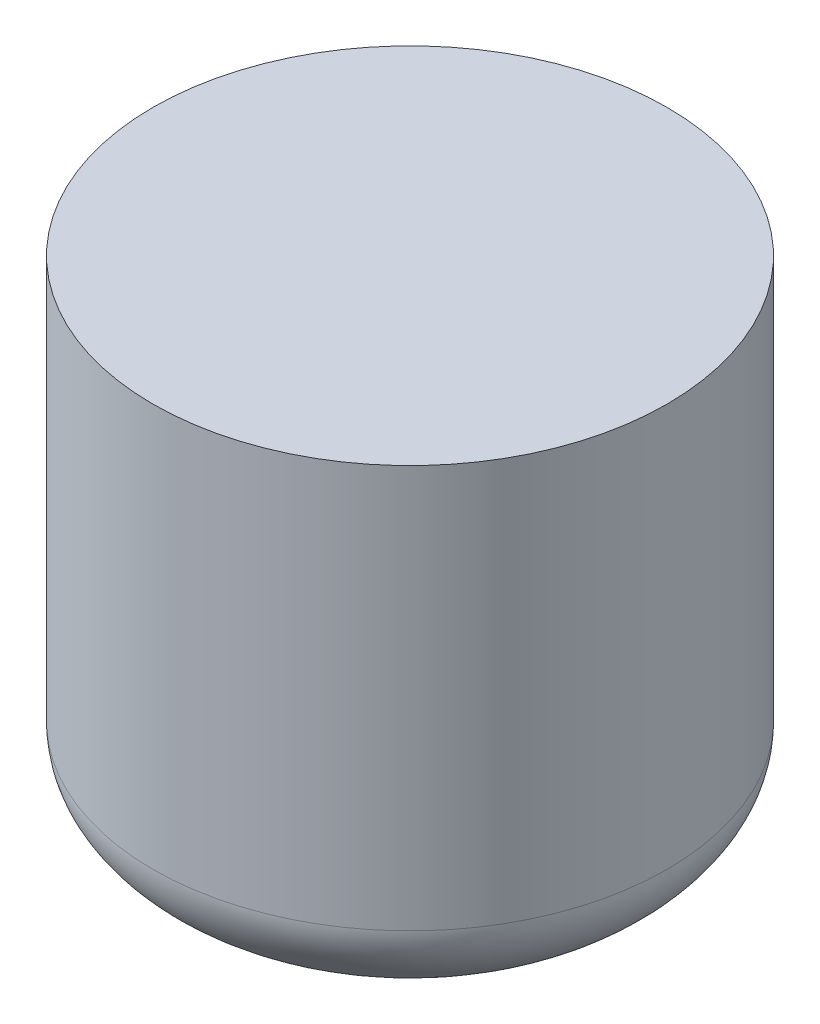
SolidWorks part; units mm, degrees
ref_plane "Front Plane" through (0, 0, 0) normal (0, 0, 1) x (1, 0, 0)
ref_plane "Top Plane" through (0, 0, 0) normal (0, 1, 0) x (1, 0, 0)
ref_plane "Right Plane" through (0, 0, 0) normal (1, 0, 0) x (0, 0, -1)
sketch "Sketch1" plane through (0, 0, 0) normal (0, 0, 1) x (1, 0, 0)
  line L1 (0, 109.4994) -> (69.85, 109.4994)
  line L2 (69.85, 109.4994) -> (69.85, 0)
  line L3 (0, -34.925) -> (0, 0) construction
  line L4 (0, 0) -> (34.925, 0) construction
  line L5 (34.925, 0) -> (69.85, 0) construction
  line L6 (0, -34.925) -> (0, 109.4994)
  ellipse E0 centre (0, 0) end of major axis (-69.85, 0) minor radius 34.925 (0, -34.925) -> (69.85, 0) ccw
  dimension "D1" = 69.85
  dimension "D2" = 109.4994
  dimension "D3" = 34.925
revolve "Revolve1" add sketch "Sketch1" angle 360 about L6
